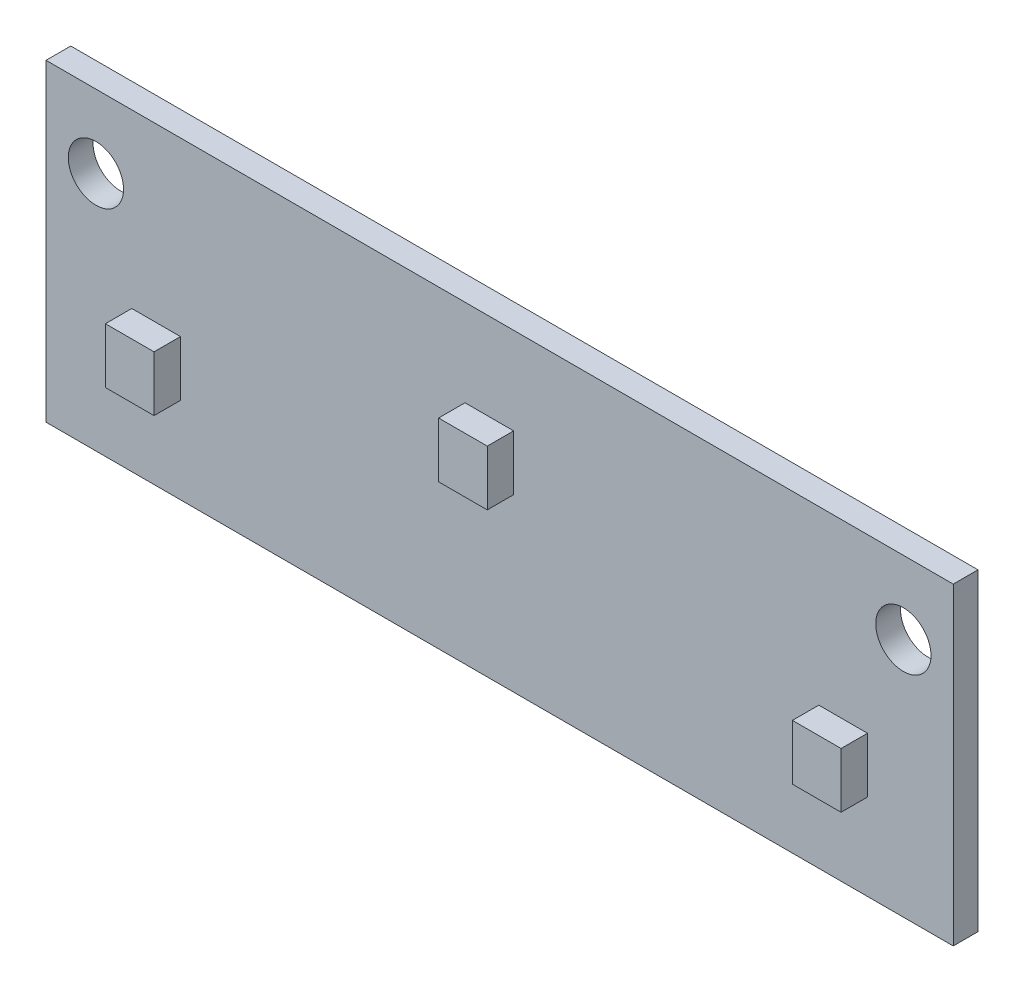
SolidWorks part; units mm, degrees
ref_plane "Front Plane" through (0, 0, 0) normal (0, 0, 1) x (1, 0, 0)
ref_plane "Top Plane" through (0, 0, 0) normal (0, 1, 0) x (1, 0, 0)
ref_plane "Right Plane" through (0, 0, 0) normal (1, 0, 0) x (0, 0, -1)
sketch "Sketch1" plane through (0, 0, 0) normal (0, 0, 1) x (1, 0, 0)
  line L1 (-27.5, -9.5) -> (27.5, -9.5)
  line L2 (-27.5, -9.5) -> (-27.5, 9.5)
  line L3 (-27.5, 9.5) -> (27.5, 9.5)
  line L4 (27.5, -9.5) -> (27.5, 9.5)
  line L5 (-27.5, -9.5) -> (27.5, 9.5) construction
  line L6 (-27.5, 9.5) -> (27.5, -9.5) construction
  point P0 (0, 0)
  dimension "D1" = 19
  dimension "D2" = 55
extrude "Boss-Extrude1" add sketch "Sketch1" along normal blind 1.5
sketch "Sketch2" plane through (0, 0, 1.5) normal (0, 0, 1) x (1, 0, 0)
  line L3 (-24.475, 6.75) -> (24.475, 6.75)
  line L4 (27.5, 9.5) -> (-27.5, 9.5) construction
  circle A0 centre (-24.475, 5.075) radius 1.675
  circle A1 centre (24.475, 5.075) radius 1.675
  dimension "D1" = 3.35
  dimension "D2" = 3.35
  dimension "D3" = 48.95
  dimension "D4" = 24.475
  dimension "D5" = 2.75
extrude "Cut-Extrude1" cut sketch "Sketch2" against normal blind 1.5 contours A0 | A1
sketch "Sketch3" plane through (0, 0, 1.5) normal (0, 0, 1) x (1, 0, 0)
  line L0 (-27.5, 9.5) -> (-27.5, -9.5) construction
  line L5 (-2.1, 0.87) -> (0.85, 0.87)
  line L6 (-2.1, 0.87) -> (-2.1, 4.22)
  line L7 (-2.1, 4.22) -> (0.85, 4.22)
  line L8 (0.85, 0.87) -> (0.85, 4.22)
  line L9 (-2.1, 0.87) -> (0.85, 4.22) construction
  line L10 (-2.1, 4.22) -> (0.85, 0.87) construction
  line L11 (19.35, -4.28) -> (22.3, -4.28)
  line L12 (19.35, -4.28) -> (19.35, -0.93)
  line L13 (19.35, -0.93) -> (22.3, -0.93)
  line L14 (22.3, -4.28) -> (22.3, -0.93)
  line L15 (19.35, -4.28) -> (22.3, -0.93) construction
  line L16 (19.35, -0.93) -> (22.3, -4.28) construction
  line L17 (-22.3, -4.28) -> (-19.35, -4.28)
  line L18 (-22.3, -4.28) -> (-22.3, -0.93)
  line L19 (-22.3, -0.93) -> (-19.35, -0.93)
  line L20 (-19.35, -4.28) -> (-19.35, -0.93)
  line L21 (-22.3, -4.28) -> (-19.35, -0.93) construction
  line L22 (-22.3, -0.93) -> (-19.35, -4.28) construction
  line L24 (-27.5, -9.5) -> (27.5, -9.5) construction
  point P0 (-20.825, -2.605)
  point P4 (-0.625, 2.545)
  point P9 (20.825, -2.605)
  dimension "D1" = 3.35
  dimension "D2" = 2.95
  dimension "D3" = 2.95
  dimension "D4" = 2.95
  dimension "D5" = 3.35
  dimension "D6" = 3.35
  dimension "D7" = 5.2
  dimension "D8" = 25.4
  dimension "D9" = 46.85
  dimension "D10" = 1.8
  dimension "D11" = 5.22
  dimension "D12" = 5.22
extrude "Boss-Extrude2" add sketch "Sketch3" along normal blind 1.6 contours L18 L17 L20 L19 | L6 L5 L8 L7 | L12 L11 L14 L13
